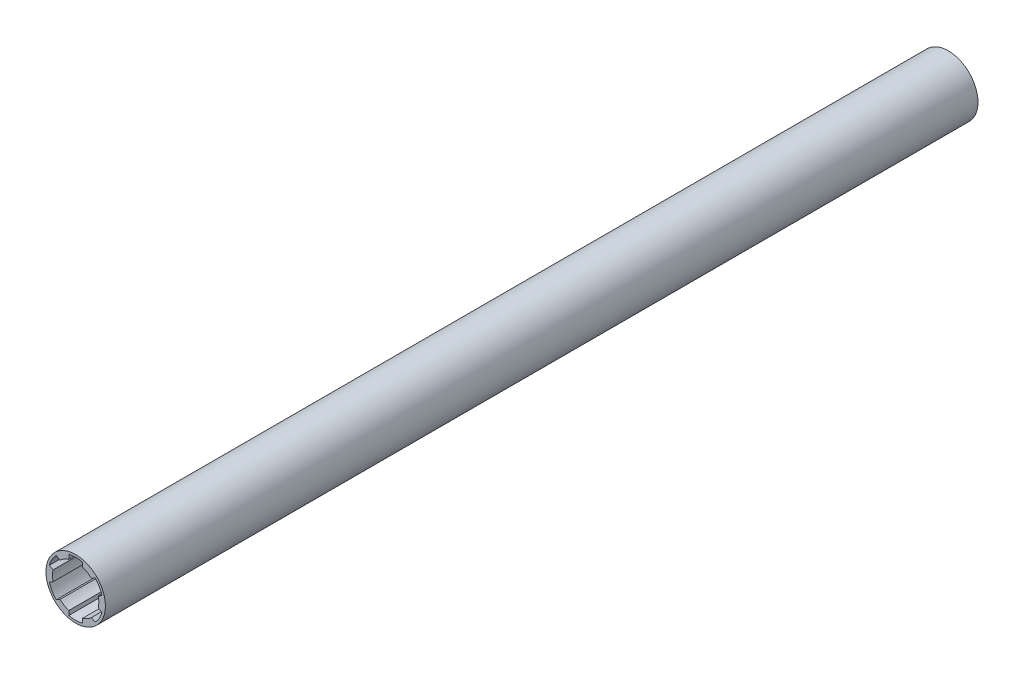
SolidWorks part; units mm, degrees
ref_plane "Front Plane" through (0, 0, 0) normal (0, 0, 1) x (1, 0, 0)
ref_plane "Top Plane" through (0, 0, 0) normal (0, 1, 0) x (1, 0, 0)
ref_plane "Right Plane" through (0, 0, 0) normal (1, 0, 0) x (0, 0, -1)
sketch "Sketch1" plane through (0, 0, 0) normal (0, 0, 1) x (1, 0, 0)
  line L0 (12.468, 12.2444) -> (10.0834, 10.8677)
  line L1 (16.838, 4.6754) -> (14.4534, 3.2986)
  line L2 (-4.37, 16.9198) -> (-4.37, 14.1663)
  line L3 (4.37, 16.9198) -> (4.37, 14.1663)
  line L4 (16.838, -4.6754) -> (14.4534, -3.2986)
  line L5 (12.468, -12.2444) -> (10.0834, -10.8677)
  line L6 (4.37, -16.9198) -> (4.37, -14.1663)
  line L7 (-4.37, -16.9198) -> (-4.37, -14.1663)
  line L8 (-12.468, -12.2444) -> (-10.0834, -10.8677)
  line L9 (-16.838, -4.6754) -> (-14.4534, -3.2986)
  line L10 (-16.838, 4.6754) -> (-14.4534, 3.2986)
  line L11 (-12.468, 12.2444) -> (-10.0834, 10.8677)
  arc A0 (4.37, 16.9198) -> (-4.37, 16.9198) centre (0, 0) ccw
  arc A1 (-4.37, 14.1663) -> (-10.0834, 10.8677) centre (0, 0) ccw
  arc A2 (16.838, 4.6754) -> (12.468, 12.2444) centre (0, 0) ccw
  arc A3 (12.468, -12.2444) -> (16.838, -4.6754) centre (0, 0) ccw
  arc A4 (-4.37, -16.9198) -> (4.37, -16.9198) centre (0, 0) ccw
  arc A5 (-16.838, -4.6754) -> (-12.468, -12.2444) centre (0, 0) ccw
  arc A6 (-12.468, 12.2444) -> (-16.838, 4.6754) centre (0, 0) ccw
  circle A7 centre (0, 0) radius 19.04
  arc A8 (10.0834, 10.8677) -> (4.37, 14.1663) centre (0, 0) ccw
  arc A9 (4.37, -14.1663) -> (14.4534, 3.2986) centre (0, 0) ccw
  arc A10 (-10.0834, -10.8677) -> (-4.37, -14.1663) centre (0, 0) ccw
  arc A11 (-14.4534, 3.2986) -> (-14.4534, -3.2986) centre (0, 0) ccw
  point P8 (0, 17.475)
  dimension "D1" = 34.95
  dimension "D2" = 29.65
  dimension "D4" = 38.08
  dimension "D3" = 6
extrude "Boss-Extrude1" add sketch "Sketch1" along normal blind 558.8 contours A7 A11 L10 A6 L11 A1 L2 A0 L3 A8 L0 A2 L1 A9 L4 A3 L5 L6 A4 L7 A10 L8 A5 L9
